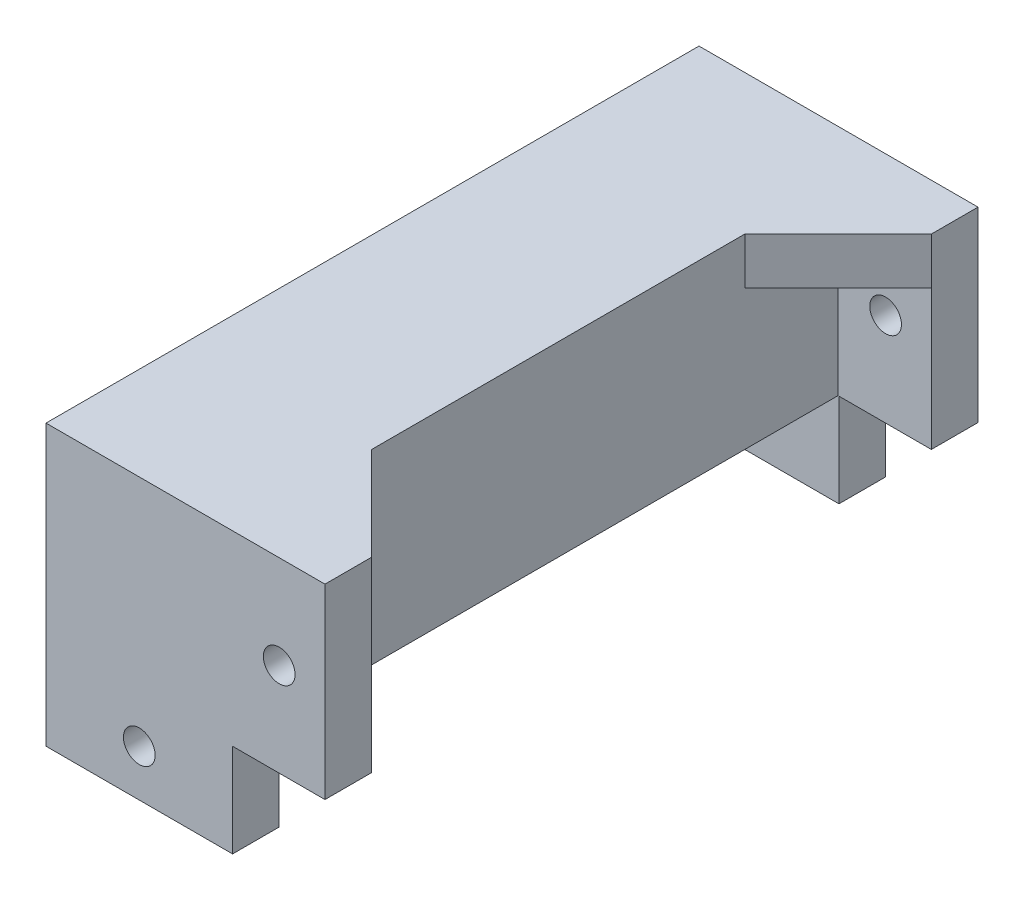
SolidWorks part; units mm, degrees
material "Custom Plastic"
ref_plane "Front Plane" through (0, 0, 0) normal (0, 0, 1) x (1, 0, 0)
ref_plane "Top Plane" through (0, 0, 0) normal (0, 1, 0) x (1, 0, 0)
ref_plane "Right Plane" through (0, 0, 0) normal (1, 0, 0) x (0, 0, -1)
sketch "Sketch1" plane through (0, 0, 246.4764) normal (0, 0, 1) x (1, 0, 0)
  line L1 (-42.5534, 305.4353) -> (-22.5534, 305.4353)
  line L2 (-42.5534, 305.4353) -> (-42.5534, 285.4353)
  line L3 (-42.5534, 285.4353) -> (-22.5534, 285.4353)
  line L4 (-42.5534, 305.4353) -> (-42.5534, 0.6353)
  line L5 (-42.5534, 0.6353) -> (262.2466, 0.6353)
  line L6 (262.2466, 0.6353) -> (262.2466, 305.4353)
  line L7 (262.2466, 305.4353) -> (-42.5534, 305.4353)
  line L8 (-42.5534, 305.4353) -> (-42.5534, 0.6353)
  line L9 (-42.5534, 0.6353) -> (262.2466, 0.6353)
  line L10 (262.2466, 0.6353) -> (262.2466, 305.4353)
  line L11 (262.2466, 305.4353) -> (-42.5534, 305.4353)
  line L12 (-22.5534, 305.4353) -> (-22.5534, 285.4353)
  line L13 (-22.5534, 285.4353) -> (-12.6493, 285.4353)
  line L14 (-22.5534, 285.4353) -> (-22.5534, 305.4353)
  line L15 (-22.5534, 305.4353) -> (-12.6493, 305.4353)
  line L16 (-12.6493, 285.4353) -> (-12.6493, 305.4353)
  line L705 (-22.5534, 285.4353) -> (-42.5534, 285.4353)
  line L706 (-22.5534, 285.4353) -> (-22.5534, 275.4353)
  line L707 (-22.5534, 275.4353) -> (-42.5534, 275.4353)
  line L708 (-42.5534, 285.4353) -> (-42.5534, 275.4353)
  circle A0 centre (-32.5534, 280.4353) radius 1.7 construction
  circle A1 centre (-17.5534, 295.4353) radius 1.7 construction
  circle A2 centre (-32.5534, 280.4353) radius 1.7
  circle A3 centre (-17.5534, 295.4353) radius 1.7
  dimension "D1" = 0
extrude "Boss-Extrude1" add sketch "Sketch1" along normal blind 70
sketch "Sketch2" plane through (-42.5534, 0, 0) normal (-1, 0, 0) x (0, 0, 1)
  line L0 (281.4764, 275.4353) -> (281.4764, 285.4353) construction
  line L1 (281.4764, 285.4353) -> (311.4764, 285.4353) construction
  line L3 (311.4764, 285.4353) -> (251.4764, 285.4353)
  line L4 (246.4764, 305.4353) -> (246.4764, 275.4353)
  line L5 (246.4764, 275.4353) -> (316.4764, 275.4353)
  line L6 (316.4764, 275.4353) -> (316.4764, 305.4353)
  line L7 (316.4764, 305.4353) -> (246.4764, 305.4353)
  line L8 (246.4764, 305.4353) -> (246.4764, 275.4353)
  line L9 (246.4764, 275.4353) -> (316.4764, 275.4353)
  line L10 (316.4764, 275.4353) -> (316.4764, 305.4353)
  line L11 (316.4764, 305.4353) -> (246.4764, 305.4353)
  line L12 (311.4764, 285.4353) -> (311.4764, 275.4353)
  line L13 (311.4764, 275.4353) -> (251.4764, 275.4353)
  line L14 (251.4764, 285.4353) -> (251.4764, 275.4353)
  dimension "D1" = 0
extrude "Cut-Extrude1" cut sketch "Sketch2" against normal blind 25 contours L3 L14 L9 L12
sketch "Sketch3" plane through (-42.5534, 0, 0) normal (-1, 0, 0) x (0, 0, 1)
  line L0 (311.4764, 275.4353) -> (301.4764, 285.4353)
  line L1 (251.4764, 275.4353) -> (261.4764, 285.4353)
  line L9 (311.4764, 275.4353) -> (316.4764, 275.4353)
  line L10 (316.4764, 275.4353) -> (316.4764, 305.4353)
  line L11 (316.4764, 305.4353) -> (246.4764, 305.4353)
  line L12 (246.4764, 305.4353) -> (246.4764, 275.4353)
  line L14 (251.4764, 275.4353) -> (251.4764, 285.4353)
  line L15 (251.4764, 285.4353) -> (311.4764, 285.4353)
  line L17 (311.4764, 275.4353) -> (316.4764, 275.4353)
  line L18 (316.4764, 275.4353) -> (316.4764, 305.4353)
  line L19 (316.4764, 305.4353) -> (246.4764, 305.4353)
  line L20 (246.4764, 305.4353) -> (246.4764, 275.4353)
  line L23 (261.4764, 285.4353) -> (301.4764, 285.4353)
  line L24 (311.4764, 285.4353) -> (311.4764, 275.4353)
  line L25 (246.4764, 275.4353) -> (251.4764, 275.4353)
  line L26 (246.4764, 275.4353) -> (251.4764, 275.4353)
  dimension "D1" = 0
extrude "Boss-Extrude2" add sketch "Sketch3" against normal blind 5
sketch "Sketch4" plane through (0, 305.4353, 0) normal (0, 1, 0) x (1, 0, 0)
  line L0 (-12.6493, -281.4764) -> (-22.6493, -281.4764) construction
  line L1 (-22.6493, -281.4764) -> (-22.6493, -311.4764) construction
  line L3 (-22.6493, -311.4764) -> (-12.6493, -311.4764)
  line L4 (-42.5534, -246.4764) -> (-42.5534, -316.4764)
  line L5 (-42.5534, -316.4764) -> (-12.6493, -316.4764)
  line L6 (-12.6493, -316.4764) -> (-12.6493, -246.4764)
  line L7 (-12.6493, -246.4764) -> (-42.5534, -246.4764)
  line L8 (-42.5534, -246.4764) -> (-42.5534, -316.4764)
  line L9 (-42.5534, -316.4764) -> (-12.6493, -316.4764)
  line L10 (-12.6493, -316.4764) -> (-12.6493, -246.4764)
  line L11 (-12.6493, -246.4764) -> (-42.5534, -246.4764)
  line L12 (-22.6493, -311.4764) -> (-22.6493, -251.4764)
  line L13 (-22.6493, -251.4764) -> (-12.6493, -251.4764)
  line L14 (-12.6493, -311.4764) -> (-12.6493, -251.4764)
  line M10 (-12.6493, -316.4764) -> (-12.6493, -246.4764)
  dimension "D1" = 0
extrude "Cut-Extrude2" cut sketch "Sketch4" against normal blind 20 contours L13 L12 L3 M10
sketch "Sketch5" plane through (0, 305.4353, 0) normal (0, 1, 0) x (1, 0, 0)
  line L0 (-12.6493, -311.4764) -> (-22.6493, -301.4764)
  line L1 (-12.6493, -251.4764) -> (-22.6493, -261.4764)
  line L8 (-22.6493, -251.4764) -> (-12.6493, -251.4764)
  line L9 (-12.6493, -251.4764) -> (-12.6493, -246.4764)
  line L10 (-12.6493, -246.4764) -> (-42.5534, -246.4764)
  line L11 (-42.5534, -246.4764) -> (-42.5534, -316.4764)
  line L12 (-42.5534, -316.4764) -> (-12.6493, -316.4764)
  line L15 (-22.6493, -311.4764) -> (-22.6493, -251.4764)
  line L17 (-12.6493, -251.4764) -> (-12.6493, -246.4764)
  line L18 (-12.6493, -246.4764) -> (-42.5534, -246.4764)
  line L19 (-42.5534, -246.4764) -> (-42.5534, -316.4764)
  line L20 (-42.5534, -316.4764) -> (-12.6493, -316.4764)
  line L23 (-22.6493, -301.4764) -> (-22.6493, -261.4764)
  line L24 (-12.6493, -316.4764) -> (-12.6493, -311.4764)
  line L25 (-12.6493, -316.4764) -> (-12.6493, -311.4764)
  line L26 (-12.6493, -311.4764) -> (-22.6493, -311.4764)
  dimension "D1" = 0
extrude "Boss-Extrude3" add sketch "Sketch5" against normal blind 5
